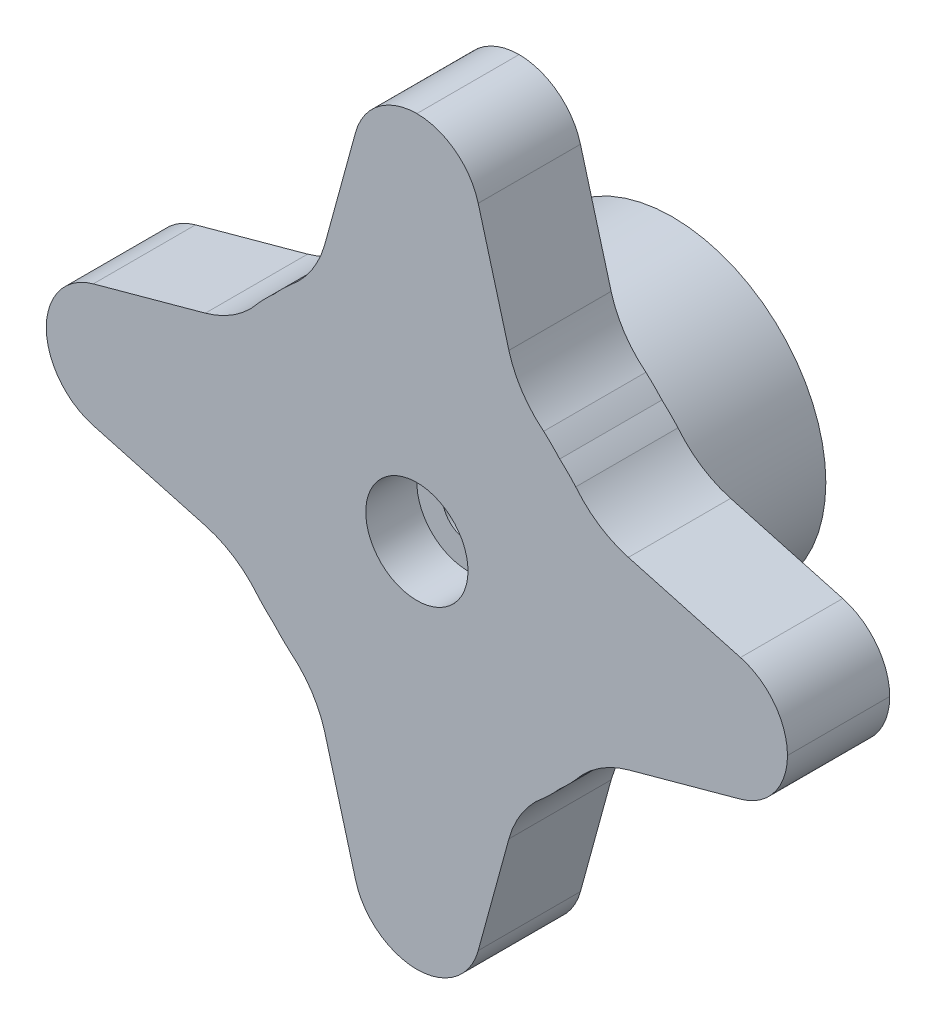
SolidWorks part; units mm, degrees
ref_plane "Front Plane" through (0, 0, 0) normal (0, 0, 1) x (1, 0, 0)
ref_plane "Top Plane" through (0, 0, 0) normal (0, 1, 0) x (1, 0, 0)
ref_plane "Right Plane" through (0, 0, 0) normal (1, 0, 0) x (0, 0, -1)
sketch "Sketch1" plane through (0, 0, 0) normal (0, 0, 1) x (1, 0, 0)
  line L0 (0, 7.25) -> (0, -7.25) construction
  line L1 (-7.4733, 0) -> (7.4733, 0) construction
  line L2 (0, 0) -> (5.2095, -5.2095) construction
  line L3 (1.2, -6.33) -> (1.8, -4.1378)
  line L4 (6.33, -1.2) -> (4.1378, -1.8)
  line L5 (0, 0) -> (-5.2095, -5.2095) construction
  line L6 (-6.33, -1.2) -> (-4.1378, -1.8)
  line L7 (-1.2, -6.33) -> (-1.8, -4.1378)
  line L8 (0, 0) -> (-5.2095, 5.2095) construction
  line L9 (0, 0) -> (5.2095, 5.2095) construction
  line L10 (-1.2, 6.33) -> (-1.8, 4.1378)
  line L11 (-6.33, 1.2) -> (-4.1378, 1.8)
  line L12 (6.33, 1.2) -> (4.1378, 1.8)
  line L13 (1.2, 6.33) -> (1.8, 4.1378)
  arc A0 (0, -7.25) -> (1.2, -6.33) centre (-0.0057, -6) ccw
  arc A1 (1.8, -4.1378) -> (2.48, -3.1078) centre (3.7276, -4.671) cw
  arc A2 (2.48, -3.1078) -> (2.7942, -2.7942) centre (-0.1839, -0.1239) ccw
  arc A3 (7.25, 0) -> (6.33, -1.2) centre (6, 0.0057) cw
  arc A4 (4.1378, -1.8) -> (3.1078, -2.48) centre (4.671, -3.7276) ccw
  arc A5 (3.1078, -2.48) -> (2.7942, -2.7942) centre (0.1239, 0.1839) cw
  arc A6 (-3.1078, -2.48) -> (-2.7942, -2.7942) centre (-0.1239, 0.1839) ccw
  arc A7 (-4.1378, -1.8) -> (-3.1078, -2.48) centre (-4.671, -3.7276) cw
  arc A8 (-7.25, 0) -> (-6.33, -1.2) centre (-6, 0.0057) ccw
  arc A9 (-2.48, -3.1078) -> (-2.7942, -2.7942) centre (0.1839, -0.1239) cw
  arc A10 (-1.8, -4.1378) -> (-2.48, -3.1078) centre (-3.7276, -4.671) ccw
  arc A11 (0, -7.25) -> (-1.2, -6.33) centre (0.0057, -6) cw
  arc A12 (0, 7.25) -> (-1.2, 6.33) centre (0.0057, 6) ccw
  arc A13 (-1.8, 4.1378) -> (-2.48, 3.1078) centre (-3.7276, 4.671) cw
  arc A14 (-2.48, 3.1078) -> (-2.7942, 2.7942) centre (0.1839, 0.1239) ccw
  arc A15 (-7.25, 0) -> (-6.33, 1.2) centre (-6, -0.0057) cw
  arc A16 (-4.1378, 1.8) -> (-3.1078, 2.48) centre (-4.671, 3.7276) ccw
  arc A17 (-3.1078, 2.48) -> (-2.7942, 2.7942) centre (-0.1239, -0.1839) cw
  arc A18 (3.1078, 2.48) -> (2.7942, 2.7942) centre (0.1239, -0.1839) ccw
  arc A19 (4.1378, 1.8) -> (3.1078, 2.48) centre (4.671, 3.7276) cw
  arc A20 (7.25, 0) -> (6.33, 1.2) centre (6, -0.0057) ccw
  arc A21 (2.48, 3.1078) -> (2.7942, 2.7942) centre (-0.1839, 0.1239) cw
  arc A22 (1.8, 4.1378) -> (2.48, 3.1078) centre (3.7276, 4.671) ccw
  arc A23 (0, 7.25) -> (1.2, 6.33) centre (-0.0057, 6) cw
  point P6 (0, 0)
  point P11 (0, 0)
  point P66 (0, 0)
  dimension "D4" = 1.25
  dimension "D10" = 2
  dimension "D13" = 4
  dimension "D1" = 7.25
  dimension "D2" = 45
  dimension "D3" = 1.2
  dimension "D5" = 0.92
  dimension "D6" = 0.6
  dimension "D7" = 2.1922
  dimension "D8" = 0.68
  dimension "D9" = 1.03
extrude "Boss-Extrude1" add sketch "Sketch1" along normal blind 2
sketch "Sketch2" plane through (0, 0, 0) normal (0, 0, -1) x (-1, 0, 0)
  circle A0 centre (0, 0) radius 3
  circle A1 centre (0, 0) radius 2.5
  dimension "D1" = 6
  dimension "D2" = 5
extrude "Boss-Extrude2" add sketch "Sketch2" along normal blind 3
sketch "Sketch3" plane through (0, 0, 2) normal (0, 0, 1) x (1, 0, 0)
  circle A0 centre (0, 0) radius 1
  dimension "D1" = 2
extrude "Cut-Extrude1" cut sketch "Sketch3" against normal blind 1
sketch "Sketch4" plane through (0, 0, 1) normal (0, 0, 1) x (1, 0, 0)
  circle A0 centre (0, 0) radius 0.5
  dimension "D1" = 1
extrude "Cut-Extrude2" cut sketch "Sketch4" against normal blind 1
